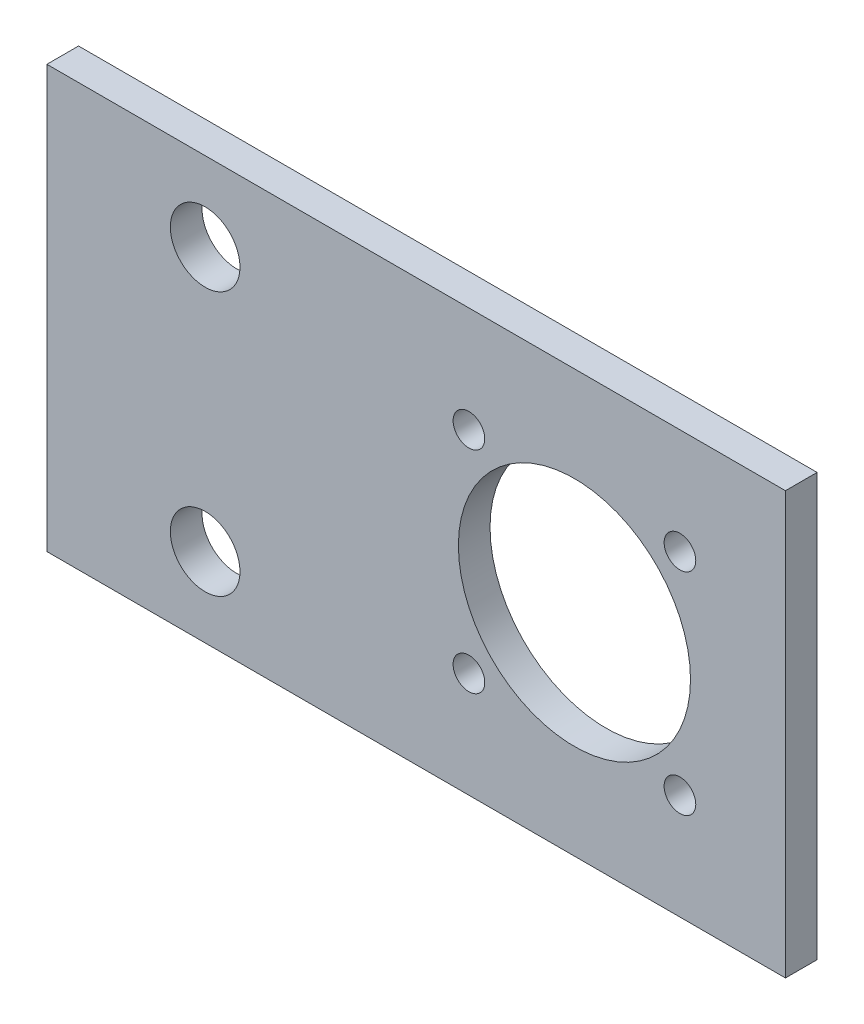
SolidWorks part; units mm, degrees
ref_plane "Ebene vorne" through (0, 0, 0) normal (0, 0, 1) x (1, 0, 0)
ref_plane "Ebene oben" through (0, 0, 0) normal (0, 1, 0) x (1, 0, 0)
ref_plane "Ebene rechts" through (0, 0, 0) normal (1, 0, 0) x (0, 0, -1)
sketch "Skizze1" plane through (0, 0, 0) normal (0, 0, 1) x (1, 0, 0)
  line L1 (-15.55, 310) -> (54.45, 310)
  line L2 (-15.55, 310) -> (-15.55, 350)
  line L3 (-15.55, 350) -> (54.45, 350)
  line L4 (54.45, 310) -> (54.45, 350)
  dimension "D1" = 70
  dimension "D2" = 40
extrude "Aufsatz-Linear austragen1" add sketch "Skizze1" along normal blind 3 contours L1 L4 L3 L2
hole_wizard "Ø3.0 (3) Durchmesser Bohrung2" positions "Skizze2" profile "Skizze3" hole size "Ø3.0" standard "DIN" end condition through all
sketch "Skizze2" plane through (0, 0, 3) normal (0, 0, 1) x (1, 0, 0)
  line L0 (-15.55, 310) -> (-15.55, 350) construction
  line L1 (-15.55, 350) -> (54.45, 350) construction
  point P0 (24.45, 340)
  point P2 (44.45, 340)
  point P4 (44.45, 320)
  point P6 (24.45, 320)
  point P16 (0, 0)
  dimension "D1" = 20
  dimension "D2" = 20
  dimension "D3" = 40
  dimension "D4" = 20
  dimension "D5" = 10
  dimension "D6" = 10
sketch "Skizze3" plane through (24.45, 340, 3) normal (1, 0, 0) x (0, -1, 0)
  line L0 (0, 0) -> (0, 3)
  line L1 (0, 3) -> (1.5, 3)
  line L2 (1.5, 3) -> (1.5, 0)
  line L5 (1.5, 0) -> (0, 0)
  line L11 (0, -6.35) -> (0, 107.95) construction
  dimension "Bohrerdurchmesser" = 3
  dimension "Bohrungstiefe" = 3
hole_wizard "Durchgangsloch für M61" positions "Skizze5" profile "Skizze6" hole size "M6" standard "DIN" end condition through all
sketch "Skizze5" plane through (0, 0, 3) normal (0, 0, 1) x (1, 0, 0)
  line L0 (-15.55, 350) -> (54.45, 350) construction
  line L1 (-15.55, 310) -> (-15.55, 350) construction
  point P0 (-0.55, 342.5)
  point P2 (-0.55, 317.5)
  dimension "D1" = 25
  dimension "D2" = 7.5
  dimension "D3" = 15
sketch "Skizze6" plane through (-0.55, 342.5, 3) normal (1, 0, 0) x (0, -1, 0)
  line L0 (0, 0) -> (0, 3)
  line L1 (0, 3) -> (3.3, 3)
  line L2 (3.3, 3) -> (3.3, 0)
  line L5 (3.3, 0) -> (0, 0)
  line L11 (0, -6.35) -> (0, 107.95) construction
  dimension "Bohrerdurchmesser" = 6.6
  dimension "Bohrungstiefe" = 3
hole_wizard "Ø22.0 (22) Durchmesser Bohrung1" positions "Skizze7" profile "Skizze8" hole size "Ø22.0" standard "DIN" end condition through all
sketch "Skizze7" plane through (0, 0, 0) normal (0, 0, -1) x (-1, 0, 0)
  line L0 (-54.45, 310) -> (-54.45, 350) construction
  line L1 (15.55, 310) -> (-54.45, 310) construction
  point P0 (-34.45, 330)
  dimension "D1" = 20
  dimension "D2" = 20
sketch "Skizze8" plane through (34.45, 330, 0) normal (1, 0, 0) x (0, 1, 0)
  line L0 (0, 0) -> (0, 3)
  line L1 (0, 3) -> (11, 3)
  line L2 (11, 3) -> (11, 0)
  line L5 (11, 0) -> (0, 0)
  line L11 (0, -6.35) -> (0, 107.95) construction
  dimension "Bohrerdurchmesser" = 22
  dimension "Bohrungstiefe" = 3
